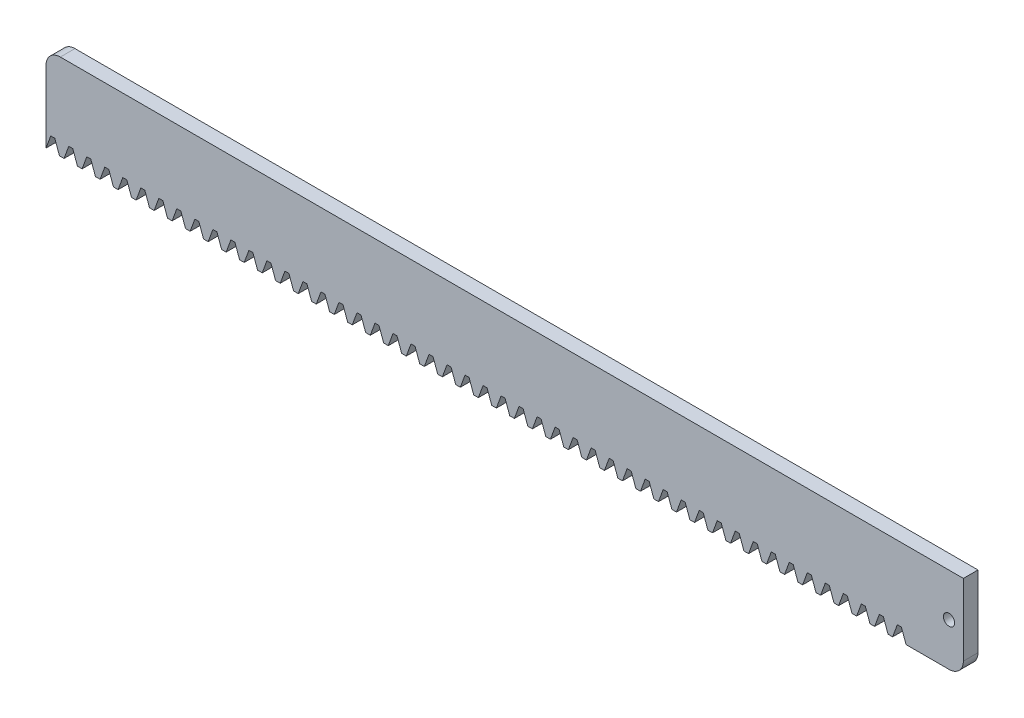
SolidWorks part; units mm, degrees
material "PC High Viscosity"
ref_plane "Front Plane" through (0, 0, 0) normal (0, 0, 1) x (1, 0, 0)
ref_plane "Top Plane" through (0, 0, 0) normal (0, 1, 0) x (1, 0, 0)
ref_plane "Right Plane" through (0, 0, 0) normal (1, 0, 0) x (0, 0, -1)
sketch "Sketch1" plane through (0, 0, 0) normal (0, 0, 1) x (1, 0, 0)
  line L2 (0, 0) -> (0, 38.1)
  line L3 (0, 38.1) -> (40.5308, 38.1)
  line L4 (406.4, 0) -> (406.4, 38.1)
  line L8 (40.5308, 38.1) -> (406.4, 38.1)
  line L9 (0, 0) -> (406.4, 0)
  line L11 (406.4, 22.7162) -> (400.05, 26.3823) construction
  line L12 (400.05, 26.3823) -> (393.7, 22.7162) construction
  line L13 (393.7, 22.7162) -> (393.7, 15.3838) construction
  line L14 (393.7, 15.3838) -> (400.05, 11.7177) construction
  line L15 (400.05, 11.7177) -> (406.4, 15.3838) construction
  line L16 (406.4, 15.3838) -> (406.4, 22.7162) construction
  line L19 (590.55, 0) -> (590.55, 10.0162) construction
  line L20 (590.55, 10.0162) -> (76.2, 10.0162) construction
  line L21 (76.2, 10.0162) -> (76.2, 0) construction
  circle A0 centre (400.05, 19.05) radius 2.4892
  circle A1 centre (400.05, 19.05) radius 6.35 construction
  dimension "D5" = 4.9784
  dimension "D7" = 12.7
  dimension "D1" = 406.4
  dimension "D2" = 38.1
extrude "Boss-Extrude1" add sketch "Sketch1" along normal blind 6.477
fillet "Fillet2" radius 6.35 2 edges at (0, 38.1, 3.2385) (406.4, 0, 3.2385)
sketch "Sketch2" plane through (0, 0, 6.477) normal (0, 0, 1) x (1, 0, 0)
  line L0 (381, 0) -> (-134.0943, 0)
  line L1 (-134.0943, 0) -> (-134.0943, 5.715)
  line L2 (-134.0943, 5.715) -> (381, 5.715)
  line L3 (381, 5.715) -> (381, 0)
  line L5 (380.0755, 2.54) -> (371.911, 2.54) construction
  line L6 (381, 0) -> (378.9199, 5.715)
  line L8 (375.0688, 0) -> (381, 0)
  line L10 (378.9199, 5.715) -> (377.1488, 5.715)
  line L11 (381, 0) -> (375.0688, 0)
  line L12 (375.0688, 0) -> (377.1488, 5.715)
  line L13 (377.1488, 5.715) -> (378.9199, 5.715)
  line L14 (381, 0) -> (375.0688, 0)
  line L15 (377.1488, 5.715) -> (378.9199, 5.715)
  line L16 (381, 0) -> (375.0688, 0)
  line L17 (375.0688, 0) -> (381, 0)
  line L19 (378.9199, 5.715) -> (377.1488, 5.715) construction
  line L20 (375.0688, 0) -> (381, 0) construction
  line L22 (406.4, 0) -> (406.4, 38.1) construction
  line L23 (0, 0) -> (406.4, 0) construction
  point P8 (375.9932, 2.54)
  point P16 (380.0755, 2.54)
  dimension "D1" = 70
  dimension "D2" = 2.54
  dimension "D3" = 3.175
  dimension "D4" = 70
  dimension "D5" = 1.7711
  dimension "D6" = 25.4
  dimension "D7" = 515.0943
extrude "Cut-Extrude1" cut sketch "Sketch2" against normal through all contours L12 L0 L8 L6 L2
pattern_linear "LPattern1" count 61 spacing 7.9796 along (-1, 0, 0) of "Cut-Extrude1"
